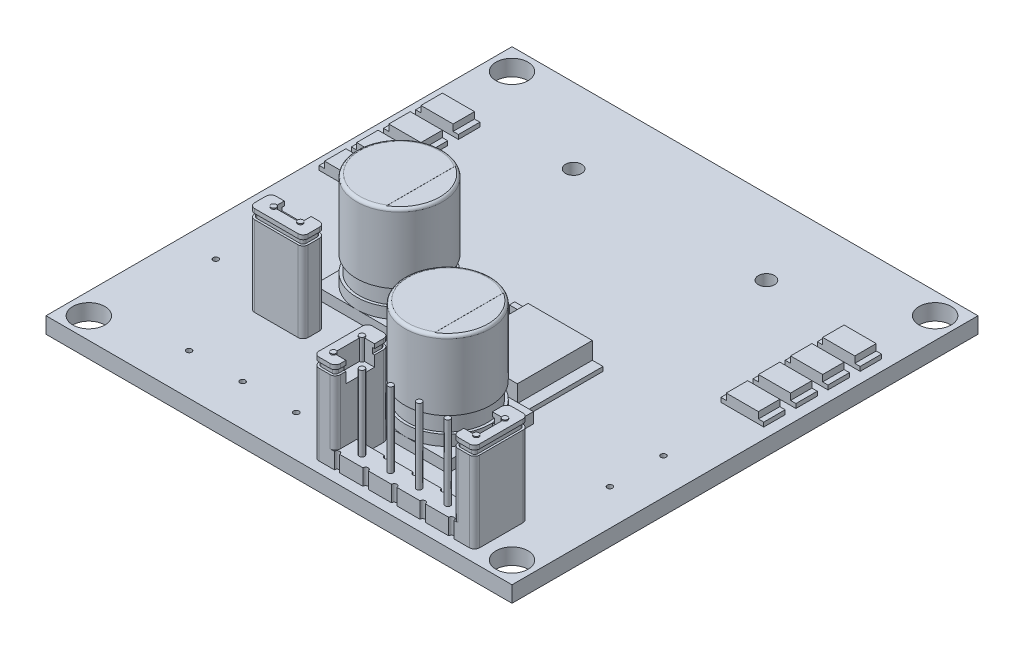
SolidWorks part; units mm, degrees
ref_plane "Ön Düzlem" through (0, 0, 0) normal (0, 0, 1) x (1, 0, 0)
ref_plane "Üst Düzlem" through (0, 0, 0) normal (0, 1, 0) x (1, 0, 0)
ref_plane "Sağ Düzlem" through (0, 0, 0) normal (1, 0, 0) x (0, 0, -1)
sketch "Çizim1" plane through (0, 0, 0) normal (0, 1, 0) x (1, 0, 0)
  line L0 (0, 0) -> (0, 21.75) construction
  line L1 (-21.75, 21.75) -> (21.75, 21.75)
  line L2 (-21.75, 21.75) -> (-21.75, -21.75)
  line L3 (-21.75, -21.75) -> (21.75, -21.75)
  line L4 (21.75, 21.75) -> (21.75, -21.75)
  line L5 (-21.75, 21.75) -> (21.75, -21.75) construction
  line L6 (-21.75, -21.75) -> (21.75, 21.75) construction
  line L7 (0, 21.75) -> (0, 0) construction
  line L8 (0, 0) -> (21.75, 0) construction
  circle A0 centre (-19.75, 19.75) radius 1.5
  circle A1 centre (19.75, 19.75) radius 1.5
  circle A2 centre (19.75, -19.75) radius 1.5
  circle A3 centre (-19.75, -19.75) radius 1.5
  point P0 (0, 0)
  point P17 (0, 0)
  dimension "D3" = 3
  dimension "D5" = 2
  dimension "D1" = 43.5
  dimension "D2" = 43.5
  dimension "D4" = 2
extrude "Yükseklik-Ekstrüzyon1" add sketch "Çizim1" along normal blind 1.5
sketch "Çizim2" plane through (0, 1.5, 0) normal (0, 1, 0) x (1, 0, 0)
  line L0 (0, 21.75) -> (0, 0) construction
  line L1 (21.75, 21.75) -> (-21.75, 21.75) construction
  line L2 (-21.75, 14.75) -> (21.75, 14.75) construction
  line L3 (-21.75, 21.75) -> (-21.75, -21.75) construction
  line L4 (21.75, -21.75) -> (21.75, 21.75) construction
  circle A0 centre (-9, 14.75) radius 0.75
  circle A1 centre (9, 14.75) radius 0.75
  dimension "D2" = 9
  dimension "D3" = 1.5
  dimension "D1" = 9
  dimension "D4" = 7
extrude "Kes-Ekstrüzyon1" cut sketch "Çizim2" against normal blind 10
sketch "Çizim3" plane through (0, 1.5, 0) normal (0, 1, 0) x (1, 0, 0)
  line L0 (-21.75, -3.75) -> (21.75, -3.75) construction
  line L1 (-21.75, 21.75) -> (-21.75, -21.75) construction
  line L2 (21.75, -21.75) -> (21.75, 21.75) construction
  line L3 (-21.75, -21.75) -> (21.75, -21.75) construction
  line L4 (-6.75, 21.75) -> (-6.75, -21.75) construction
  line L5 (21.75, 21.75) -> (-21.75, 21.75) construction
  line L6 (5.75, 21.75) -> (5.75, -21.75) construction
  line L7 (-10.75, 0.25) -> (-2.75, 0.25)
  line L8 (-10.75, 0.25) -> (-10.75, -7.75)
  line L9 (-10.75, -7.75) -> (-2.75, -7.75)
  line L10 (-2.75, 0.25) -> (-2.75, -7.75)
  line L11 (-10.75, 0.25) -> (-2.75, -7.75) construction
  line L12 (-10.75, -7.75) -> (-2.75, 0.25) construction
  line L13 (-21.75, -11.75) -> (21.75, -11.75) construction
  line L15 (1.75, -7.75) -> (9.75, -7.75)
  line L16 (1.75, -7.75) -> (1.75, -15.75)
  line L17 (1.75, -15.75) -> (9.75, -15.75)
  line L18 (9.75, -7.75) -> (9.75, -15.75)
  line L19 (1.75, -7.75) -> (9.75, -15.75) construction
  line L20 (1.75, -15.75) -> (9.75, -7.75) construction
  point P12 (-6.75, -3.75)
  point P21 (5.75, -11.75)
  dimension "D1" = 18
  dimension "D2" = 15
  dimension "D3" = 8
  dimension "D4" = 8
  dimension "D5" = 16
  dimension "D6" = 10
  dimension "D7" = 8
  dimension "D8" = 8
extrude "Yükseklik-Ekstrüzyon2" add sketch "Çizim3" along normal blind 1
sketch "Çizim4" plane through (0, 2.5, 0) normal (0, 1, 0) x (1, 0, 0)
  line L0 (-10.75, 0.25) -> (-2.75, -7.75) construction
  line L1 (1.75, -7.75) -> (9.75, -15.75) construction
  circle A0 centre (-6.75, -3.75) radius 4
  circle A1 centre (5.75, -11.75) radius 4
extrude "Yükseklik-Ekstrüzyon3" add sketch "Çizim4" along normal blind 1
sketch "Çizim5" plane through (0, 3.5, 0) normal (0, 1, 0) x (1, 0, 0)
  circle A0 centre (-6.75, -3.75) radius 3.75
  circle A1 centre (5.75, -11.75) radius 3.75
  dimension "D1" = 7.5
  dimension "D2" = 7.5
extrude "Yükseklik-Ekstrüzyon4" add sketch "Çizim5" along normal blind 1.5
sketch "Çizim6" plane through (0, 5, 0) normal (0, 1, 0) x (1, 0, 0)
  circle A0 centre (-6.75, -3.75) radius 4
  circle A1 centre (5.75, -11.75) radius 4
extrude "Yükseklik-Ekstrüzyon5" add sketch "Çizim6" along normal blind 6.5
fillet "Radyus1" radius 0.3 2 edges at (5.75, 11.5, 15.75) (-6.75, 11.5, 7.75)
sketch "Çizim7" plane through (0, 11.5, 0) normal (0, 1, 0) x (1, 0, 0)
  line L0 (-6.75, -3.75) -> (-6.75, 0.25) construction
  line L1 (-4.7498, -0.286) -> (-4.7498, -7.214)
  line L2 (5.75, -11.75) -> (5.75, -7.75) construction
  line L3 (7.75, -8.2859) -> (7.75, -15.2141)
  arc A0 (-4.7498, -7.214) -> (-4.7498, -0.286) centre (-6.75, -3.75) ccw
  arc A1 (7.75, -15.2141) -> (7.75, -8.2859) centre (5.75, -11.75) ccw
  dimension "D1" = 2.0002
  dimension "D2" = 2
extrude "Kes-Ekstrüzyon2" cut sketch "Çizim7" against normal blind 0.01
sketch "Çizim8" plane through (0, 1.5, 0) normal (0, 1, 0) x (1, 0, 0)
  line L0 (21.75, -20.75) -> (15.3333, -20.75) construction
  line L1 (21.75, -21.75) -> (21.75, 21.75) construction
  line L2 (-21.75, 21.75) -> (-21.75, -21.75) construction
  line L3 (-21.75, -21.75) -> (21.75, -21.75) construction
  line L4 (17.25, -21.75) -> (17.25, 21.75) construction
  line L5 (21.75, 21.75) -> (-21.75, 21.75) construction
  line L6 (4.25, -18.75) -> (6.8333, -18.75)
  line L7 (16.7735, -20.75) -> (15.3333, -20.75)
  line L8 (17.25, -20.2735) -> (17.25, -16.2265)
  line L9 (16.7735, -15.75) -> (15.7265, -15.75)
  line L10 (2.25, -20.2735) -> (2.25, -16.2265)
  line L11 (4.25, -16.2265) -> (4.25, -18.75)
  line L12 (15.25, -16.2265) -> (15.25, -18.75)
  line L13 (3.7735, -15.75) -> (2.7265, -15.75)
  line L15 (6.8333, -20.75) -> (4.6667, -20.75)
  line L16 (6.8333, -20.75) -> (4.6667, -20.75) construction
  line L17 (2.25, -19.75) -> (17.25, -19.75) construction
  line L18 (16.425, -19.75) -> (16.425, -15.75) construction
  line L19 (10, -18.75) -> (12.1667, -18.75)
  line L20 (9.5, -20.75) -> (7.3333, -20.75)
  line L21 (9.5, -20.75) -> (7.3333, -20.75) construction
  line L22 (12.6667, -18.75) -> (15.25, -18.75)
  line L23 (12.1667, -20.75) -> (10, -20.75) construction
  line L24 (12.1667, -20.75) -> (10, -20.75)
  line L25 (14.8333, -20.75) -> (12.6667, -20.75) construction
  line L26 (14.8333, -20.75) -> (12.6667, -20.75)
  line L27 (4.1667, -20.75) -> (2.7265, -20.75)
  line L28 (4.1667, -20.75) -> (-21.75, -20.75) construction
  line L29 (7.3333, -18.75) -> (9.5, -18.75)
  circle A0 centre (19.75, -19.75) radius 1.5 construction
  arc A1 (15.25, -16.2265) -> (15.7265, -15.75) centre (15.7265, -16.2265) cw
  arc A2 (17.25, -16.2265) -> (16.7735, -15.75) centre (16.7735, -16.2265) ccw
  arc A3 (16.7735, -20.75) -> (17.25, -20.2735) centre (16.7735, -20.2735) ccw
  arc A4 (2.7265, -20.75) -> (2.25, -20.2735) centre (2.7265, -20.2735) cw
  arc A5 (4.25, -16.2265) -> (3.7735, -15.75) centre (3.7735, -16.2265) ccw
  arc A6 (2.7265, -15.75) -> (2.25, -16.2265) centre (2.7265, -16.2265) ccw
  circle A7 centre (11.085, -19.75) radius 0.25
  circle A8 centre (13.755, -19.75) radius 0.25
  circle A9 centre (16.425, -19.75) radius 0.25
  circle A10 centre (16.425, -17.08) radius 0.25
  arc A11 (9.5, -18.75) -> (10, -18.75) centre (9.75, -18.75) ccw
  arc A12 (12.1667, -18.75) -> (12.6667, -18.75) centre (12.4167, -18.75) ccw
  arc A13 (10, -20.75) -> (9.5, -20.75) centre (9.75, -20.75) ccw
  arc A14 (12.6667, -20.75) -> (12.1667, -20.75) centre (12.4167, -20.75) ccw
  arc A15 (15.3333, -20.75) -> (14.8333, -20.75) centre (15.0833, -20.75) ccw
  circle A16 centre (3.075, -17.08) radius 0.25
  circle A17 centre (3.075, -19.75) radius 0.25
  arc A18 (4.1667, -20.75) -> (4.6667, -20.75) centre (4.4167, -20.75) cw
  circle A19 centre (5.745, -19.75) radius 0.25
  arc A20 (6.8333, -20.75) -> (7.3333, -20.75) centre (7.0833, -20.75) cw
  arc A21 (7.3333, -18.75) -> (6.8333, -18.75) centre (7.0833, -18.75) cw
  circle A22 centre (8.415, -19.75) radius 0.25
  point P26 (17.25, -15.75)
  point P29 (17.25, -20.75)
  point P32 (2.25, -20.75)
  point P35 (4.25, -15.75)
  dimension "D2" = 2.5
  dimension "D8" = 0.4765
  dimension "D13" = 0.5
  dimension "D14" = 2.67
  dimension "D15" = 2.67
  dimension "D16" = 2.67
  dimension "D17" = 0.5
  dimension "D18" = 0.5
  dimension "D1" = 1
  dimension "D3" = 5
  dimension "D4" = 2
  dimension "D5" = 15
  dimension "D6" = 2
  dimension "D7" = 2
  dimension "D11" = 1
extrude "Yükseklik-Ekstrüzyon6" add sketch "Çizim8" along normal blind 1.5
sketch "Çizim9" plane through (0, 3, 0) normal (0, 1, 0) x (1, 0, 0)
  circle A0 centre (3.075, -17.08) radius 0.25
  circle A1 centre (3.075, -19.75) radius 0.25
  circle A2 centre (5.745, -19.75) radius 0.25
  circle A3 centre (8.415, -19.75) radius 0.25
  circle A4 centre (11.085, -19.75) radius 0.25
  circle A5 centre (13.755, -19.75) radius 0.25
  circle A6 centre (16.425, -19.75) radius 0.25
  circle A7 centre (16.425, -17.08) radius 0.25
extrude "Kes-Ekstrüzyon3" cut sketch "Çizim9" against normal blind 5
sketch "Çizim10" plane through (0, 3, 0) normal (0, 1, 0) x (1, 0, 0)
  circle A0 centre (3.075, -17.08) radius 0.25
  circle A1 centre (3.075, -19.75) radius 0.25
  circle A2 centre (5.745, -19.75) radius 0.25
  circle A3 centre (8.415, -19.75) radius 0.25
  circle A4 centre (11.085, -19.75) radius 0.25
  circle A5 centre (13.755, -19.75) radius 0.25
  circle A6 centre (16.425, -19.75) radius 0.25
  circle A7 centre (16.425, -17.08) radius 0.25
extrude "Yükseklik-Ekstrüzyon7" add sketch "Çizim10" along normal blind 7 and the other way blind 3.5
sketch "Çizim11" plane through (0, 3, 0) normal (0, 1, 0) x (1, 0, 0)
  line L0 (9.75, -19) -> (9.75, -20.5) construction
  line L1 (3.25, -15.75) -> (3.25, -20.75) construction
  line L2 (3.7735, -15.75) -> (2.7265, -15.75) construction
  line L3 (2.7265, -20.75) -> (4.1667, -20.75) construction
  line L4 (16.7735, -20.75) -> (15.7265, -20.75)
  line L5 (2.7265, -15.75) -> (3.7735, -15.75)
  line L6 (2.25, -16.2265) -> (2.25, -20.2735)
  line L7 (2.7265, -20.75) -> (3.7735, -20.75)
  line L8 (4.25, -16.2265) -> (4.25, -20.2735)
  line L9 (2.25, -15.75) -> (4.25, -20.75) construction
  line L10 (2.25, -20.75) -> (4.25, -15.75) construction
  line L11 (15.25, -16.2265) -> (15.25, -20.2735)
  line L12 (16.7735, -15.75) -> (15.7265, -15.75)
  line L13 (17.25, -16.2265) -> (17.25, -20.2735)
  arc A0 (9.5, -18.75) -> (10, -18.75) centre (9.75, -18.75) ccw construction
  arc A1 (10, -20.75) -> (9.5, -20.75) centre (9.75, -20.75) ccw construction
  arc A2 (3.7735, -20.75) -> (4.25, -20.2735) centre (3.7735, -20.2735) ccw
  arc A3 (2.25, -20.2735) -> (2.7265, -20.75) centre (2.7265, -20.2735) ccw
  arc A4 (3.7735, -15.75) -> (4.25, -16.2265) centre (3.7735, -16.2265) cw
  arc A5 (2.7265, -15.75) -> (2.25, -16.2265) centre (2.7265, -16.2265) ccw
  circle A6 centre (3.075, -17.08) radius 0.25
  circle A7 centre (3.075, -19.75) radius 0.25
  circle A8 centre (16.425, -19.75) radius 0.25
  circle A9 centre (16.425, -17.08) radius 0.25
  arc A10 (15.7265, -20.75) -> (15.25, -20.2735) centre (15.7265, -20.2735) cw
  arc A11 (15.7265, -15.75) -> (15.25, -16.2265) centre (15.7265, -16.2265) ccw
  arc A12 (17.25, -20.2735) -> (16.7735, -20.75) centre (16.7735, -20.2735) cw
  arc A13 (16.7735, -15.75) -> (17.25, -16.2265) centre (16.7735, -16.2265) cw
  point P14 (3.25, -18.25)
  dimension "D1" = 0.4765
extrude "Yükseklik-Ekstrüzyon8" add sketch "Çizim11" along normal blind 5
sketch "Çizim12" plane through (0, 8, 0) normal (0, 1, 0) x (1, 0, 0)
  line L0 (3.25, -16.8151) -> (3.25, -19.6849) construction
  line L3 (3.325, -17.08) -> (4.25, -17.08)
  line L4 (2.7265, -15.75) -> (3.7735, -15.75)
  line L5 (2.25, -16.2265) -> (2.25, -20.2735)
  line L6 (2.7265, -20.75) -> (3.7735, -20.75)
  line L7 (4.25, -16.2265) -> (4.25, -17.08)
  line L8 (2.25, -15.75) -> (4.25, -20.75) construction
  line L9 (2.25, -20.75) -> (4.25, -15.75) construction
  line L10 (3.325, -19.75) -> (4.25, -19.75)
  line L11 (4.25, -19.75) -> (4.25, -20.2735)
  line L12 (3.075, -17.33) -> (3.075, -19.5)
  line L13 (9.75, -19) -> (9.75, -20.5) construction
  line L14 (16.175, -17.08) -> (15.25, -17.08)
  line L15 (15.25, -16.2265) -> (15.25, -17.08)
  line L16 (16.7735, -15.75) -> (15.7265, -15.75)
  line L17 (17.25, -16.2265) -> (17.25, -20.2735)
  line L18 (16.7735, -20.75) -> (15.7265, -20.75)
  line L19 (15.25, -19.75) -> (15.25, -20.2735)
  line L20 (16.175, -19.75) -> (15.25, -19.75)
  line L21 (16.425, -17.33) -> (16.425, -19.5)
  arc A0 (3.7735, -20.75) -> (4.25, -20.2735) centre (3.7735, -20.2735) ccw
  arc A1 (2.25, -20.2735) -> (2.7265, -20.75) centre (2.7265, -20.2735) ccw
  arc A2 (3.7735, -15.75) -> (4.25, -16.2265) centre (3.7735, -16.2265) cw
  arc A3 (2.7265, -15.75) -> (2.25, -16.2265) centre (2.7265, -16.2265) ccw
  arc A4 (3.325, -17.08) -> (3.075, -17.33) centre (3.075, -17.08) ccw
  arc A5 (3.075, -19.5) -> (3.325, -19.75) centre (3.075, -19.75) ccw
  arc A6 (9.5, -18.75) -> (10, -18.75) centre (9.75, -18.75) ccw construction
  arc A7 (10, -20.75) -> (9.5, -20.75) centre (9.75, -20.75) ccw construction
  arc A8 (16.175, -17.08) -> (16.425, -17.33) centre (16.425, -17.08) cw
  arc A9 (15.7265, -15.75) -> (15.25, -16.2265) centre (15.7265, -16.2265) ccw
  arc A10 (16.7735, -15.75) -> (17.25, -16.2265) centre (16.7735, -16.2265) cw
  arc A11 (17.25, -20.2735) -> (16.7735, -20.75) centre (16.7735, -20.2735) cw
  arc A12 (15.7265, -20.75) -> (15.25, -20.2735) centre (15.7265, -20.2735) cw
  arc A13 (16.425, -19.5) -> (16.175, -19.75) centre (16.425, -19.75) cw
  point P6 (3.25, -18.25)
  dimension "D1" = 0.4765
extrude "Yükseklik-Ekstrüzyon10" add sketch "Çizim12" along normal blind 1
sketch "Çizim13" plane through (0, 9, 0) normal (0, 1, 0) x (1, 0, 0)
  line L0 (3.25, -15.75) -> (3.25, -15.757) construction
  line L1 (2.7265, -15.75) -> (3.7735, -15.75) construction
  line L2 (2.7265, -20.75) -> (4.1667, -20.75) construction
  line L3 (3.075, -17.33) -> (3.075, -19.5)
  line L8 (2.2382, -15.757) -> (2.322, -15.9636) construction
  line L9 (2.2382, -20.743) -> (2.322, -20.5364) construction
  line L10 (3.325, -17.08) -> (4.0618, -17.08)
  line L11 (3.325, -19.75) -> (4.0618, -19.75)
  line L12 (2.4382, -16.2335) -> (2.4382, -20.2665)
  line L13 (2.7147, -20.543) -> (3.7853, -20.543)
  line L14 (4.0618, -16.2335) -> (4.0618, -17.08)
  line L15 (2.7147, -15.957) -> (3.7853, -15.957)
  line L16 (2.4382, -16.2498) -> (4.178, -20.5364) construction
  line L17 (4.0618, -19.75) -> (4.0618, -20.2665)
  line L18 (3.25, -15.957) -> (3.25, -20.75) construction
  line L19 (4.178, -15.9636) -> (4.2618, -15.757) construction
  line L20 (9.75, -19) -> (9.75, -20.5) construction
  line L21 (16.7853, -15.957) -> (15.7147, -15.957)
  line L22 (2.4382, -20.2502) -> (4.0618, -16.2498) construction
  line L23 (17.0618, -16.2335) -> (17.0618, -20.2665)
  line L24 (16.7853, -20.543) -> (15.7147, -20.543)
  line L25 (15.4382, -19.75) -> (15.4382, -20.2665)
  line L26 (16.175, -19.75) -> (15.4382, -19.75)
  line L27 (16.425, -17.33) -> (16.425, -19.5)
  line L28 (16.175, -17.08) -> (15.4382, -17.08)
  line L29 (15.4382, -16.2335) -> (15.4382, -17.08)
  arc A4 (3.325, -17.08) -> (3.075, -17.33) centre (3.075, -17.08) ccw
  arc A5 (3.075, -19.5) -> (3.325, -19.75) centre (3.075, -19.75) ccw
  arc A6 (2.4382, -20.2665) -> (2.7147, -20.543) centre (2.7147, -20.2665) ccw
  arc A7 (3.7853, -20.543) -> (4.0618, -20.2665) centre (3.7853, -20.2665) ccw
  arc A8 (3.7853, -15.957) -> (4.0618, -16.2335) centre (3.7853, -16.2335) cw
  arc A9 (2.7147, -15.957) -> (2.4382, -16.2335) centre (2.7147, -16.2335) ccw
  arc A10 (9.5, -18.75) -> (10, -18.75) centre (9.75, -18.75) ccw construction
  arc A11 (10, -20.75) -> (9.5, -20.75) centre (9.75, -20.75) ccw construction
  arc A12 (15.7147, -15.957) -> (15.4382, -16.2335) centre (15.7147, -16.2335) ccw
  arc A13 (16.7853, -15.957) -> (17.0618, -16.2335) centre (16.7853, -16.2335) cw
  arc A14 (17.0618, -20.2665) -> (16.7853, -20.543) centre (16.7853, -20.2665) cw
  arc A15 (15.7147, -20.543) -> (15.4382, -20.2665) centre (15.7147, -20.2665) cw
  arc A16 (16.425, -19.5) -> (16.175, -19.75) centre (16.425, -19.75) cw
  arc A17 (16.175, -17.08) -> (16.425, -17.33) centre (16.425, -17.08) cw
  point P6 (3.25, -18.25)
extrude "Yükseklik-Ekstrüzyon11" add sketch "Çizim13" along normal blind 0.5
sketch "Çizim14" plane through (0, 9.5, 0) normal (0, 1, 0) x (1, 0, 0)
  line L0 (3.25, -15.957) -> (3.25, -20.543) construction
  line L1 (3.7853, -15.957) -> (2.7147, -15.957) construction
  line L2 (2.7147, -20.543) -> (3.7853, -20.543) construction
  line L3 (4.25, -17.08) -> (3.325, -17.08)
  line L4 (2.7265, -15.75) -> (3.7735, -15.75)
  line L5 (2.25, -16.2265) -> (2.25, -20.2735)
  line L6 (2.7265, -20.75) -> (3.7735, -20.75)
  line L7 (4.25, -16.2265) -> (4.25, -17.08)
  line L8 (2.25, -15.75) -> (4.25, -20.75) construction
  line L9 (2.25, -20.75) -> (4.25, -15.75) construction
  line L10 (3.075, -17.33) -> (3.075, -19.5)
  line L11 (3.325, -19.75) -> (4.25, -19.75)
  line L12 (4.25, -19.75) -> (4.25, -20.2735)
  line L13 (9.75, -19) -> (9.75, -20.5) construction
  line L14 (15.25, -17.08) -> (16.175, -17.08)
  line L15 (15.25, -16.2265) -> (15.25, -17.08)
  line L16 (16.7735, -15.75) -> (15.7265, -15.75)
  line L17 (17.25, -16.2265) -> (17.25, -20.2735)
  line L18 (16.7735, -20.75) -> (15.7265, -20.75)
  line L19 (15.25, -19.75) -> (15.25, -20.2735)
  line L20 (16.175, -19.75) -> (15.25, -19.75)
  line L21 (16.425, -17.33) -> (16.425, -19.5)
  arc A0 (3.7735, -15.75) -> (4.25, -16.2265) centre (3.7735, -16.2265) cw
  arc A1 (2.7265, -15.75) -> (2.25, -16.2265) centre (2.7265, -16.2265) ccw
  arc A2 (3.7735, -20.75) -> (4.25, -20.2735) centre (3.7735, -20.2735) ccw
  arc A3 (2.25, -20.2735) -> (2.7265, -20.75) centre (2.7265, -20.2735) ccw
  arc A4 (3.325, -17.08) -> (3.075, -17.33) centre (3.075, -17.08) ccw
  arc A5 (3.075, -19.5) -> (3.325, -19.75) centre (3.075, -19.75) ccw
  arc A6 (9.5, -18.75) -> (10, -18.75) centre (9.75, -18.75) ccw construction
  arc A7 (10, -20.75) -> (9.5, -20.75) centre (9.75, -20.75) ccw construction
  arc A8 (16.175, -17.08) -> (16.425, -17.33) centre (16.425, -17.08) cw
  arc A9 (15.7265, -15.75) -> (15.25, -16.2265) centre (15.7265, -16.2265) ccw
  arc A10 (16.7735, -15.75) -> (17.25, -16.2265) centre (16.7735, -16.2265) cw
  arc A11 (17.25, -20.2735) -> (16.7735, -20.75) centre (16.7735, -20.2735) cw
  arc A12 (15.7265, -20.75) -> (15.25, -20.2735) centre (15.7265, -20.2735) cw
  arc A13 (16.425, -19.5) -> (16.175, -19.75) centre (16.425, -19.75) cw
  point P6 (3.25, -18.25)
  dimension "D1" = 0.4765
extrude "Yükseklik-Ekstrüzyon12" add sketch "Çizim14" along normal blind 0.4
sketch "Çizim15" plane through (0, 1.5, 0) normal (0, 1, 0) x (1, 0, 0)
  line L0 (-21.75, -17.89) -> (21.75, -17.89) construction
  line L1 (-21.75, 21.75) -> (-21.75, -21.75) construction
  line L2 (21.75, -21.75) -> (21.75, 21.75) construction
  line L3 (-21.75, -21.75) -> (21.75, -21.75) construction
  circle A0 centre (-12.25, -17.89) radius 0.25
  circle A1 centre (-7.25, -17.89) radius 0.25
  circle A2 centre (-2.25, -17.89) radius 0.25
  dimension "D2" = 0.5
  dimension "D3" = 9.5
  dimension "D4" = 5
  dimension "D5" = 5
  dimension "D1" = 3.86
extrude "Kes-Ekstrüzyon4" cut sketch "Çizim15" against normal blind 5
sketch "Çizim16" plane through (0, 1.5, 0) normal (0, 1, 0) x (1, 0, 0)
  line L0 (0, 21.75) -> (0, -21.75) construction
  line L1 (21.75, 21.75) -> (-21.75, 21.75) construction
  line L2 (-21.75, -21.75) -> (21.75, -21.75) construction
  line L3 (18.39, 21.75) -> (18.39, -21.75) construction
  line L4 (21.75, -21.75) -> (21.75, 21.75) construction
  circle A0 centre (18.39, -4.25) radius 0.25
  circle A1 centre (18.39, -9.25) radius 0.25
  circle A2 centre (-18.39, -9.25) radius 0.25
  circle A3 centre (-18.39, -4.25) radius 0.25
  dimension "D3" = 5
  dimension "D4" = 0.5
  dimension "D5" = 0.5
  dimension "D1" = 3.36
  dimension "D2" = 12.5
extrude "Kes-Ekstrüzyon5" cut sketch "Çizim16" against normal blind 7
sketch "Çizim18" plane through (0, 1.5, 0) normal (0, 1, 0) x (1, 0, 0)
  line L0 (18.75, 21.75) -> (18.75, -21.75) construction
  line L1 (21.75, 21.75) -> (-21.75, 21.75) construction
  line L2 (-21.75, -21.75) -> (21.75, -21.75) construction
  line L3 (21.75, -21.75) -> (21.75, 21.75) construction
  line L4 (18.75, 8.25) -> (21.75, 8.25) construction
  line L5 (17.25, 13.75) -> (20.25, 13.75)
  line L6 (17.25, 13.75) -> (17.25, 11.75)
  line L7 (17.25, 11.75) -> (20.25, 11.75)
  line L8 (20.25, 13.75) -> (20.25, 11.75)
  line L9 (17.25, 13.75) -> (20.25, 11.75) construction
  line L10 (17.25, 11.75) -> (20.25, 13.75) construction
  line L11 (17.25, 10.75) -> (20.25, 10.75)
  line L12 (17.25, 10.75) -> (17.25, 8.75)
  line L13 (17.25, 8.75) -> (20.25, 8.75)
  line L14 (20.25, 10.75) -> (20.25, 8.75)
  line L15 (17.25, 10.75) -> (20.25, 8.75) construction
  line L16 (17.25, 8.75) -> (20.25, 10.75) construction
  line L17 (17.25, 7.75) -> (20.25, 7.75)
  line L18 (20.25, 5.75) -> (20.25, 7.75)
  line L19 (17.25, 5.75) -> (20.25, 5.75)
  line L20 (17.25, 5.75) -> (17.25, 7.75)
  line L21 (17.25, 4.75) -> (20.25, 4.75)
  line L22 (20.25, 2.75) -> (20.25, 4.75)
  line L23 (17.25, 2.75) -> (20.25, 2.75)
  line L24 (17.25, 2.75) -> (17.25, 4.75)
  line L25 (0, 21.75) -> (0, 0) construction
  line L26 (-17.25, 2.75) -> (-17.25, 4.75)
  line L27 (-17.25, 2.75) -> (-20.25, 2.75)
  line L28 (-20.25, 2.75) -> (-20.25, 4.75)
  line L29 (-17.25, 4.75) -> (-20.25, 4.75)
  line L30 (-17.25, 5.75) -> (-17.25, 7.75)
  line L31 (-17.25, 5.75) -> (-20.25, 5.75)
  line L32 (-20.25, 5.75) -> (-20.25, 7.75)
  line L33 (-17.25, 7.75) -> (-20.25, 7.75)
  line L34 (-17.25, 8.75) -> (-20.25, 8.75)
  line L35 (-20.25, 10.75) -> (-20.25, 8.75)
  line L36 (-17.25, 10.75) -> (-20.25, 10.75)
  line L37 (-17.25, 10.75) -> (-17.25, 8.75)
  line L38 (-17.25, 11.75) -> (-20.25, 11.75)
  line L39 (-20.25, 13.75) -> (-20.25, 11.75)
  line L40 (-17.25, 13.75) -> (-20.25, 13.75)
  line L41 (-17.25, 13.75) -> (-17.25, 11.75)
  point P8 (18.75, 12.75)
  point P13 (18.75, 9.75)
  dimension "D1" = 3
  dimension "D2" = 2
  dimension "D3" = 3
  dimension "D4" = 8
  dimension "D5" = 2
  dimension "D6" = 1
  dimension "D7" = 0.5
extrude "Yükseklik-Ekstrüzyon13" add sketch "Çizim18" along normal blind 1
sketch "Çizim19" plane through (0, 1.5, 0) normal (0, 1, 0) x (1, 0, 0)
  line L0 (0, 21.75) -> (0, 0) construction
  line L1 (21.75, 21.75) -> (-21.75, 21.75) construction
  line L2 (18.75, 11.75) -> (18.75, 10.75) construction
  line L3 (17.25, 13.75) -> (16.75, 13.75)
  line L4 (17.25, 13.75) -> (17.25, 11.75)
  line L5 (17.25, 11.75) -> (16.75, 11.75)
  line L6 (16.75, 13.75) -> (16.75, 11.75)
  line L7 (20.25, 13.75) -> (20.75, 13.75)
  line L8 (20.25, 13.75) -> (20.25, 11.75)
  line L9 (20.25, 11.75) -> (20.75, 11.75)
  line L10 (20.75, 13.75) -> (20.75, 11.75)
  line L11 (17.25, 11.75) -> (20.25, 11.75) construction
  line L12 (20.25, 10.75) -> (17.25, 10.75) construction
  line L13 (18.75, 10.75) -> (18.75, 11.25) construction
  line L14 (18.75, 11.25) -> (19.385, 11.25) construction
  line L15 (20.25, 10.75) -> (20.75, 10.75)
  line L16 (20.75, 8.75) -> (20.75, 10.75)
  line L17 (20.25, 8.75) -> (20.75, 8.75)
  line L18 (20.25, 8.75) -> (20.25, 10.75)
  line L19 (17.25, 10.75) -> (16.75, 10.75)
  line L20 (16.75, 8.75) -> (16.75, 10.75)
  line L21 (17.25, 8.75) -> (16.75, 8.75)
  line L22 (17.25, 8.75) -> (17.25, 10.75)
  line L23 (18.75, 8.75) -> (18.75, 7.75) construction
  line L24 (17.25, 8.75) -> (20.25, 8.75) construction
  line L25 (20.25, 7.75) -> (17.25, 7.75) construction
  line L26 (18.75, 7.75) -> (18.75, 8.25) construction
  line L27 (18.75, 8.25) -> (19.7606, 8.25) construction
  line L28 (20.25, 7.75) -> (20.25, 5.75)
  line L29 (20.25, 7.75) -> (20.75, 7.75)
  line L30 (20.75, 7.75) -> (20.75, 5.75)
  line L31 (20.25, 5.75) -> (20.75, 5.75)
  line L32 (17.25, 7.75) -> (17.25, 5.75)
  line L33 (17.25, 7.75) -> (16.75, 7.75)
  line L34 (16.75, 7.75) -> (16.75, 5.75)
  line L35 (17.25, 5.75) -> (16.75, 5.75)
  line L36 (20.25, 4.75) -> (20.75, 4.75)
  line L37 (20.75, 2.75) -> (20.75, 4.75)
  line L38 (20.25, 2.75) -> (20.75, 2.75)
  line L39 (20.25, 2.75) -> (20.25, 4.75)
  line L40 (17.25, 4.75) -> (16.75, 4.75)
  line L41 (16.75, 2.75) -> (16.75, 4.75)
  line L42 (17.25, 2.75) -> (16.75, 2.75)
  line L43 (17.25, 2.75) -> (17.25, 4.75)
  line L44 (-20.25, 2.75) -> (-20.25, 4.75)
  line L45 (-20.25, 2.75) -> (-20.75, 2.75)
  line L46 (-20.75, 2.75) -> (-20.75, 4.75)
  line L47 (-20.25, 4.75) -> (-20.75, 4.75)
  line L48 (-17.25, 2.75) -> (-17.25, 4.75)
  line L49 (-17.25, 2.75) -> (-16.75, 2.75)
  line L50 (-16.75, 2.75) -> (-16.75, 4.75)
  line L51 (-17.25, 4.75) -> (-16.75, 4.75)
  line L52 (-20.25, 7.75) -> (-20.75, 7.75)
  line L53 (-20.75, 7.75) -> (-20.75, 5.75)
  line L54 (-20.25, 5.75) -> (-20.75, 5.75)
  line L55 (-20.25, 7.75) -> (-20.25, 5.75)
  line L56 (-17.25, 7.75) -> (-16.75, 7.75)
  line L57 (-16.75, 7.75) -> (-16.75, 5.75)
  line L58 (-17.25, 5.75) -> (-16.75, 5.75)
  line L59 (-17.25, 7.75) -> (-17.25, 5.75)
  line L60 (-17.25, 8.75) -> (-17.25, 10.75)
  line L61 (-17.25, 8.75) -> (-16.75, 8.75)
  line L62 (-16.75, 8.75) -> (-16.75, 10.75)
  line L63 (-17.25, 10.75) -> (-16.75, 10.75)
  line L64 (-20.25, 8.75) -> (-20.25, 10.75)
  line L65 (-20.25, 8.75) -> (-20.75, 8.75)
  line L66 (-20.75, 8.75) -> (-20.75, 10.75)
  line L67 (-20.25, 10.75) -> (-20.75, 10.75)
  line L68 (-20.25, 11.75) -> (-20.75, 11.75)
  line L69 (-20.75, 13.75) -> (-20.75, 11.75)
  line L70 (-20.25, 13.75) -> (-20.75, 13.75)
  line L71 (-20.25, 13.75) -> (-20.25, 11.75)
  line L72 (-17.25, 11.75) -> (-16.75, 11.75)
  line L73 (-16.75, 13.75) -> (-16.75, 11.75)
  line L74 (-17.25, 13.75) -> (-16.75, 13.75)
  line L75 (-17.25, 13.75) -> (-17.25, 11.75)
  dimension "D1" = 0.5
  dimension "D2" = 0.5
extrude "Yükseklik-Ekstrüzyon14" add sketch "Çizim19" along normal blind 0.4
sketch "Çizim20" plane through (0, 1.5, 0) normal (0, 1, 0) x (1, 0, 0)
  line L0 (21.75, -7.25) -> (-2.75, -7.25) construction
  line L1 (21.75, -21.75) -> (21.75, 21.75) construction
  line L2 (-2.75, -7.75) -> (-2.75, 0.25) construction
  line L3 (9.75, -7.75) -> (5.75, -7.75) construction
  line L4 (1.75, -7.75) -> (1.75, 21.75) construction
  line L5 (21.75, 21.75) -> (-21.75, 21.75) construction
  line L7 (1.75, -7.25) -> (7.75, -7.25)
  line L8 (1.75, -7.25) -> (1.75, -0.25)
  line L9 (1.75, -0.25) -> (7.75, -0.25)
  line L10 (7.75, -7.25) -> (7.75, -0.25)
  dimension "D1" = 0.5
  dimension "D2" = 7
  dimension "D3" = 6
extrude "Yükseklik-Ekstrüzyon15" add sketch "Çizim20" along normal blind 2
sketch "Çizim21" plane through (0, 1.5, 0) normal (0, 1, 0) x (1, 0, 0)
  line L1 (7.75, -0.25) -> (8.75, -0.25)
  line L2 (7.75, -0.25) -> (7.75, -7.25)
  line L3 (7.75, -7.25) -> (8.75, -7.25)
  line L4 (8.75, -0.25) -> (8.75, -7.25)
  dimension "D1" = 1
extrude "Yükseklik-Ekstrüzyon16" add sketch "Çizim21" along normal blind 0.4
sketch "Çizim22" plane through (0, 1.5, 0) normal (0, 1, 0) x (1, 0, 0)
  line L0 (1.75, -3.75) -> (-0.8924, -3.75) construction
  line L1 (1.75, -0.25) -> (1.75, -7.25) construction
  line L2 (1.75, -3.25) -> (1.75, -4.25)
  line L3 (0.5, -3.25) -> (1.75, -3.25)
  line L4 (0.5, -3.25) -> (0.5, -4.25)
  line L5 (0.5, -4.25) -> (1.75, -4.25)
  line L7 (0.5, -3.25) -> (1.75, -3.75) construction
  line L8 (0.5, -4.25) -> (1.75, -3.75) construction
  line L9 (1.75, -6.75) -> (0.5, -6.75)
  line L10 (1.75, -0.25) -> (0.5, -0.25)
  line L11 (1.75, -0.25) -> (1.75, -0.75)
  line L12 (1.75, -0.75) -> (0.5, -0.75)
  line L13 (0.5, -0.25) -> (0.5, -0.75)
  line L14 (0.5, -7.25) -> (0.5, -6.75)
  line L15 (1.75, -7.25) -> (0.5, -7.25)
  line L16 (1.75, -7.25) -> (1.75, -6.75)
  dimension "D1" = 0.5
extrude "Yükseklik-Ekstrüzyon17" add sketch "Çizim22" along normal blind 1.5
sketch "Çizim23" plane through (0, 1.5, 0) normal (0, 1, 0) x (1, 0, 0)
  line L0 (-12.75, -21.75) -> (-12.75, 6.8422) construction
  line L1 (-21.75, -21.75) -> (21.75, -21.75) construction
  line L2 (-21.75, 21.75) -> (-21.75, -21.75) construction
  line L3 (-21.75, -11.75) -> (21.75, -11.75) construction
  line L4 (21.75, -21.75) -> (21.75, 21.75) construction
  line L5 (-12.75, -10.75) -> (-7.75, -10.75) construction
  line L6 (-12.2735, -11.75) -> (-8.2265, -11.75)
  line L7 (-12.75, -11.2735) -> (-12.75, -10.2265)
  line L8 (-12.2735, -9.75) -> (-8.2265, -9.75)
  line L9 (-7.75, -11.2735) -> (-7.75, -10.2265)
  arc A0 (-8.2265, -11.75) -> (-7.75, -11.2735) centre (-8.2265, -11.2735) ccw
  arc A1 (-8.2265, -9.75) -> (-7.75, -10.2265) centre (-8.2265, -10.2265) cw
  arc A2 (-12.2735, -11.75) -> (-12.75, -11.2735) centre (-12.2735, -11.2735) cw
  arc A3 (-12.75, -10.2265) -> (-12.2735, -9.75) centre (-12.2735, -10.2265) cw
  circle A4 centre (-11.5, -10.75) radius 0.25
  circle A5 centre (-9, -10.75) radius 0.25
  point P16 (-7.75, -11.75)
  point P21 (-12.75, -11.75)
  point P24 (-12.75, -9.75)
  dimension "D5" = 0.4765
  dimension "D6" = 0.5
  dimension "D7" = 0.5
  dimension "D8" = 2.5
  dimension "D9" = 1.25
  dimension "D1" = 9
  dimension "D2" = 10
  dimension "D3" = 5
  dimension "D4" = 2
extrude "Yükseklik-Ekstrüzyon18" add sketch "Çizim23" along normal up to surface (7.5 mm away) up to face at (3.4312, 9, 18.283)
sketch "Çizim24" plane through (0, 1.5, 0) normal (0, 1, 0) x (1, 0, 0)
  circle A0 centre (-11.5, -10.75) radius 0.25
  circle A1 centre (-9, -10.75) radius 0.25
extrude "Yükseklik-Ekstrüzyon19" add sketch "Çizim24" along normal up to surface and the other way up to surface up to face at (11.085, 10, 20) other way up to face at (3.075, -0.5, 17.33)
sketch "Çizim25" plane through (0, 9, 0) normal (0, 1, 0) x (1, 0, 0)
  line L0 (-12.75, -10.75) -> (-11.5, -10.75) construction
  line L1 (-12.75, -10.2265) -> (-12.75, -11.2735) construction
  line L2 (-7.75, -11.2735) -> (-7.75, -10.2265) construction
  line L3 (-12.55, -10.2265) -> (-12.55, -11.2735)
  line L8 (-12.75, -9.75) -> (-7.75, -11.75) construction
  line L9 (-12.75, -11.75) -> (-7.75, -9.75) construction
  line L10 (-12.2735, -11.55) -> (-8.2265, -11.55)
  line L11 (-7.95, -10.2265) -> (-7.95, -11.2735)
  line L12 (-12.2735, -9.95) -> (-11.5, -9.95)
  line L13 (-11.5, -10.5) -> (-11.5, -9.95)
  line L14 (-9, -10.5) -> (-9, -9.95)
  line L15 (-9, -9.95) -> (-8.2265, -9.95)
  line L16 (-9, -10.75) -> (-7.75, -10.75) construction
  line L17 (-11.25, -10.75) -> (-9.25, -10.75)
  line L18 (-11.25, -10.75) -> (-9.25, -10.75) construction
  arc A4 (-12.55, -11.2735) -> (-12.2735, -11.55) centre (-12.2735, -11.2735) ccw
  arc A5 (-8.2265, -11.55) -> (-7.95, -11.2735) centre (-8.2265, -11.2735) ccw
  arc A6 (-8.2265, -9.95) -> (-7.95, -10.2265) centre (-8.2265, -10.2265) cw
  arc A7 (-12.2735, -9.95) -> (-12.55, -10.2265) centre (-12.2735, -10.2265) ccw
  arc A8 (-11.5, -10.5) -> (-11.25, -10.75) centre (-11.5, -10.75) ccw
  arc A9 (-9.25, -10.75) -> (-9, -10.5) centre (-9, -10.75) ccw
  point P6 (-10.25, -10.75)
extrude "Yükseklik-Ekstrüzyon20" add sketch "Çizim25" along normal blind 0.5
sketch "Çizim27" plane through (0, 9.5, 0) normal (0, 1, 0) x (1, 0, 0)
  line L0 (-12.55, -10.75) -> (-11.75, -10.75) construction
  line L1 (-12.55, -10.2265) -> (-12.55, -11.2735) construction
  line L2 (-7.95, -11.2735) -> (-7.95, -10.2265) construction
  line L3 (-11.5, -9.75) -> (-11.5, -10.5)
  line L4 (-12.2735, -9.75) -> (-11.5, -9.75)
  line L5 (-12.75, -10.2265) -> (-12.75, -11.2735)
  line L6 (-12.2735, -11.75) -> (-8.2265, -11.75)
  line L7 (-7.75, -10.2265) -> (-7.75, -11.2735)
  line L8 (-12.75, -9.75) -> (-7.75, -11.75) construction
  line L9 (-12.75, -11.75) -> (-7.75, -9.75) construction
  line L10 (-11.25, -10.75) -> (-9.25, -10.75)
  line L11 (-9, -10.5) -> (-9, -9.75)
  line L12 (-9, -9.75) -> (-8.2265, -9.75)
  line L13 (-11.25, -10.75) -> (-9.25, -10.75) construction
  line L14 (-8.75, -10.75) -> (-7.95, -10.75) construction
  arc A0 (-8.2265, -11.75) -> (-7.75, -11.2735) centre (-8.2265, -11.2735) ccw
  arc A1 (-12.75, -11.2735) -> (-12.2735, -11.75) centre (-12.2735, -11.2735) ccw
  arc A2 (-8.2265, -9.75) -> (-7.75, -10.2265) centre (-8.2265, -10.2265) cw
  arc A3 (-12.2735, -9.75) -> (-12.75, -10.2265) centre (-12.2735, -10.2265) ccw
  arc A4 (-11.5, -10.5) -> (-11.25, -10.75) centre (-11.5, -10.75) ccw
  arc A5 (-9.25, -10.75) -> (-9, -10.5) centre (-9, -10.75) ccw
  point P6 (-10.25, -10.75)
  dimension "D1" = 0.4765
extrude "Yükseklik-Ekstrüzyon21" add sketch "Çizim27" along normal up to surface (0.4 mm away) up to face at (3.3355, 9.9, 18.3207)
